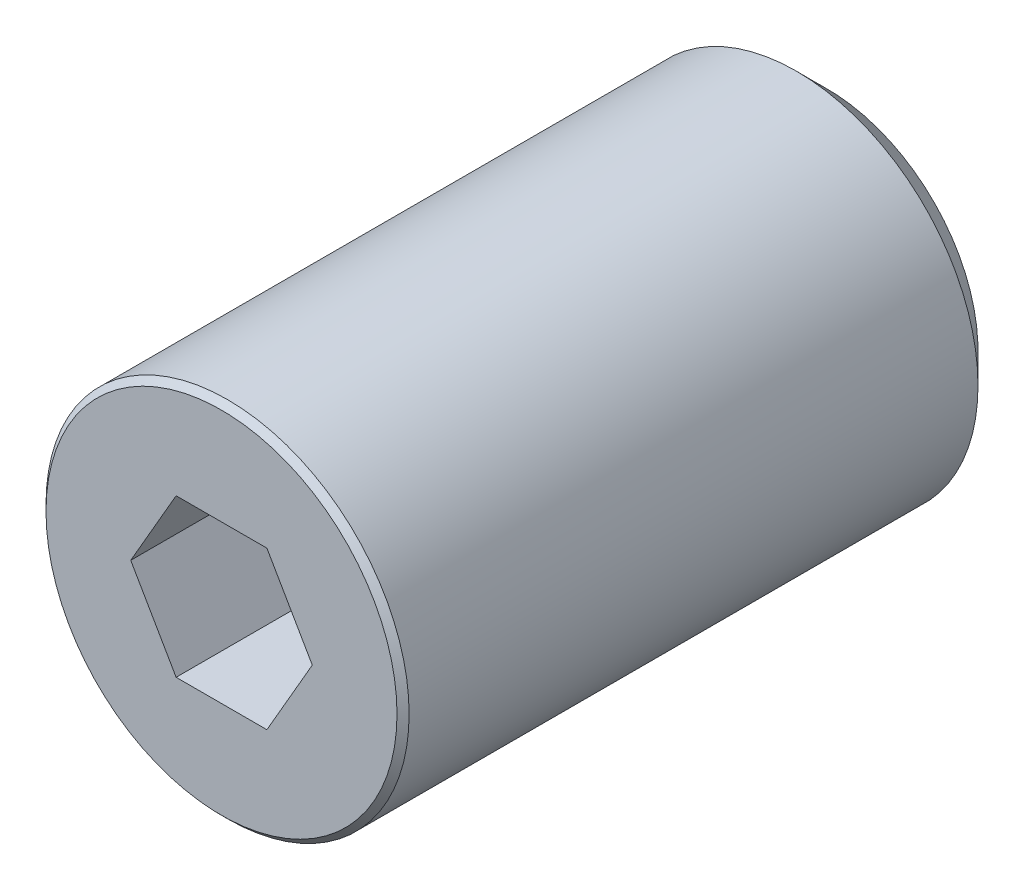
SolidWorks part; units mm, degrees
ref_plane "前视基准面" through (0, 0, 0) normal (0, 0, 1) x (1, 0, 0)
ref_plane "上视基准面" through (0, 0, 0) normal (0, 1, 0) x (1, 0, 0)
ref_plane "右视基准面" through (0, 0, 0) normal (1, 0, 0) x (0, 0, -1)
other "Configuration Table"
sketch "草图1" plane through (0, 0, 0) normal (0, 1, 0) x (1, 0, 0)
  line L0 (3, 0) -> (0, 0)
  line L1 (0, 0) -> (0, -10)
  line L2 (0, -10) -> (3, -10)
  line L3 (3, -10) -> (3, 0)
  line L4 (0, 0) -> (0, -10) construction
revolve "旋转1" add sketch "草图1" angle 360 about L4
sketch "草图2" plane through (0, 0, 10) normal (0, 0, 1) x (1, 0, 0)
  line L0 (0.75, -1.299) -> (1.5, 0)
  line L1 (1.5, 0) -> (0.75, 1.299)
  line L2 (0.75, 1.299) -> (-0.75, 1.299)
  line L3 (-0.75, 1.299) -> (-1.5, 0)
  line L4 (-1.5, 0) -> (-0.75, -1.299)
  line L5 (-0.75, -1.299) -> (0.75, -1.299)
extrude "切除-拉伸1" cut sketch "草图2" against normal blind 3
sketch "草图3" plane through (0, 0, 0) normal (0, 1, 0) x (1, 0, 0)
  line L0 (1.5, 0) -> (0, 0)
  line L1 (0, 0) -> (0, -0.5)
  line L2 (0, -0.5) -> (1.5, 0)
  line L3 (0, 0) -> (0, -0.5001) construction
revolve "切除-旋转1" cut sketch "草图3" angle 360 about L3
chamfer "倒角1" distance 0.1 angle 45 1 edges at (3, 0, 10)
chamfer "倒角2" distance 1.1258 angle 41.612 6 edges at (-1.125, -0.6495, 7) (-1.125, 0.6495, 7) (0, -1.299, 7) (0, 1.299, 7) (1.125, -0.6495, 7) (1.125, 0.6495, 7)
chamfer "倒角3" distance 0.5 angle 45 1 edges at (3, 0, 0)
